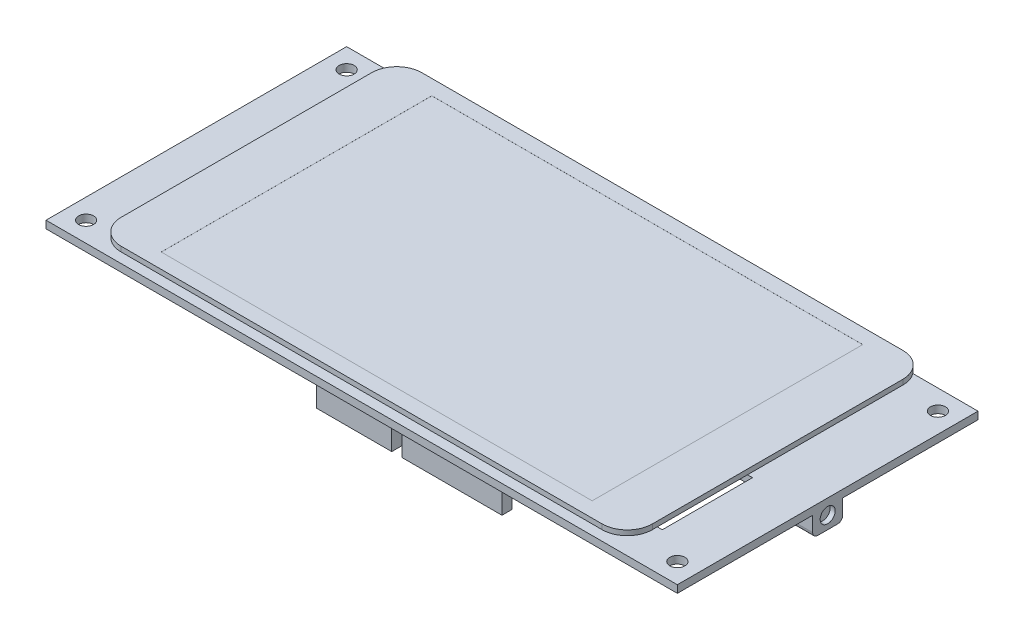
SolidWorks part; units mm, degrees
ref_plane "Front Plane" through (0, 0, 0) normal (0, 0, 1) x (1, 0, 0)
ref_plane "Top Plane" through (0, 0, 0) normal (0, 1, 0) x (1, 0, 0)
ref_plane "Right Plane" through (0, 0, 0) normal (1, 0, 0) x (0, 0, -1)
sketch "Sketch1" plane through (0, 0, 0) normal (0, 1, 0) x (1, 0, 0)
  line L0 (0, 0) -> (-26.909, 0) construction
  line L1 (-63, -30) -> (63, -30)
  line L2 (-63, -30) -> (-63, 30)
  line L3 (-63, 30) -> (63, 30)
  line L4 (63, -30) -> (63, 30)
  line L5 (-63, -30) -> (63, 30) construction
  line L6 (-63, 30) -> (63, -30) construction
  line L7 (0, 20.9021) -> (0, 0) construction
  circle A0 centre (-59, 26) radius 1.5
  circle A1 centre (-59, -26) radius 1.5
  circle A2 centre (59, -26) radius 1.5
  circle A3 centre (59, 26) radius 1.5
  point P0 (0, 0)
  dimension "D3" = 3
  dimension "D1" = 126
  dimension "D2" = 60
  dimension "D4" = 26
  dimension "D5" = 4
extrude "Boss-Extrude1" add sketch "Sketch1" along normal blind 1.5
sketch "Sketch2" plane through (0, 1.5, 0) normal (0, 1, 0) x (1, 0, 0)
  line L1 (-50, -25) -> (50, -25)
  line L2 (-50, -25) -> (-50, 25)
  line L3 (-50, 25) -> (50, 25)
  line L4 (50, -25) -> (50, 25)
  line L5 (-50, -25) -> (50, 25) construction
  line L6 (-50, 25) -> (50, -25) construction
  point P0 (0, 0)
  dimension "D1" = 100
  dimension "D2" = 50
extrude "Boss-Extrude2" add sketch "Sketch2" along normal blind 2
sketch "Sketch3" plane through (0, 3.5, 0) normal (0, 1, 0) x (1, 0, 0)
  line L0 (63, 30) -> (-63, 30) construction
  line L1 (-53, -30) -> (53, -30)
  line L2 (-53, -30) -> (-53, 30)
  line L3 (-53, 30) -> (53, 30)
  line L4 (53, -30) -> (53, 30)
  line L5 (-53, -30) -> (53, 30) construction
  line L6 (-53, 30) -> (53, -30) construction
  point P0 (0, 0)
  dimension "D1" = 106
extrude "Boss-Extrude3" add sketch "Sketch3" along normal blind 1
fillet "Fillet1" radius 5 4 edges at (-53, 4, -30) (-53, 4, 30) (53, 4, -30) (53, 4, 30)
sketch "Sketch4" plane through (0, 4.5, 0) normal (0, 1, 0) x (1, 0, 0)
  line L0 (48, 30) -> (-48, 30) construction
  line L1 (-43, -27) -> (43, -27)
  line L2 (-43, -27) -> (-43, 27)
  line L3 (-43, 27) -> (43, 27)
  line L4 (43, -27) -> (43, 27)
  line L5 (-43, -27) -> (43, 27) construction
  line L6 (-43, 27) -> (43, -27) construction
  line L7 (53, -25) -> (53, 25) construction
  point P0 (0, 0)
  dimension "D1" = 3
  dimension "D2" = 10
extrude "Cut-Extrude1" cut sketch "Sketch4" against normal blind 0.01
sketch "Sketch6" plane through (0, 0, 0) normal (0, -1, 0) x (1, 0, 0)
  line L0 (-63, 30) -> (63, 30) construction
  line L1 (34, 22) -> (52, 22)
  line L2 (34, 22) -> (34, 4)
  line L3 (34, 4) -> (52, 4)
  line L4 (52, 22) -> (52, 4)
  line L5 (63, 30) -> (63, -30) construction
  dimension "D1" = 8
  dimension "D2" = 11
  dimension "D3" = 18
  dimension "D4" = 18
extrude "Cut-Extrude2" cut sketch "Sketch6" against normal blind 1.5
sketch "Sketch7" plane through (0, 0, 0) normal (0, -1, 0) x (1, 0, 0)
  line L0 (63, 30) -> (63, -30) construction
  line L1 (3, 25) -> (23, 25)
  line L2 (3, 25) -> (3, 23)
  line L3 (3, 23) -> (23, 23)
  line L4 (23, 25) -> (23, 23)
  line L5 (-63, 30) -> (63, 30) construction
  line L7 (1, 25) -> (-14, 25)
  line L8 (1, 25) -> (1, 23)
  line L9 (1, 23) -> (-14, 23)
  line L10 (-14, 25) -> (-14, 23)
  line L11 (63, -30) -> (-63, -30) construction
  line L12 (33, -23) -> (8, -23)
  line L13 (33, -23) -> (33, -25)
  line L14 (33, -25) -> (8, -25)
  line L15 (8, -23) -> (8, -25)
  line L17 (6, -25) -> (-14, -25)
  line L18 (6, -25) -> (6, -23)
  line L19 (6, -23) -> (-14, -23)
  line L20 (-14, -25) -> (-14, -23)
  point P22 (0, -30)
  dimension "D1" = 40
  dimension "D2" = 5
  dimension "D3" = 2
  dimension "D4" = 20
  dimension "D5" = 15
  dimension "D6" = 2
  dimension "D7" = 5
  dimension "D8" = 2
  dimension "D9" = 2
  dimension "D10" = 5
  dimension "D11" = 30
  dimension "D12" = 25
  dimension "D13" = 20
  dimension "D14" = 2
  dimension "D15" = 2
  dimension "D16" = 5
extrude "Boss-Extrude4" add sketch "Sketch7" along normal blind 9
sketch "Sketch8" plane through (0, 0, -25) normal (0, 0, -1) x (-1, 0, 0)
  line L0 (-8, -9) -> (-33, -9) construction
  line L1 (-33, 0) -> (-30, 0)
  line L2 (-33, 0) -> (-33, -9)
  line L3 (-33, -9) -> (-30, -9)
  line L4 (-30, 0) -> (-30, -9)
  dimension "D1" = 3
extrude "Cut-Extrude3" cut sketch "Sketch8" against normal blind 2
sketch "Sketch9" plane through (0, 0, 0) normal (0, -1, 0) x (1, 0, 0)
  line L0 (63, 30) -> (63, -30) construction
  line L1 (58, -3) -> (63, -3)
  line L2 (58, -3) -> (58, 3)
  line L3 (58, 3) -> (63, 3)
  line L4 (63, -3) -> (63, 3)
  line L5 (58, -3) -> (63, 3) construction
  line L6 (58, 3) -> (63, -3) construction
  point P0 (60.5, 0)
  dimension "D1" = 6
  dimension "D2" = 5
extrude "Boss-Extrude5" add sketch "Sketch9" along normal blind 4
sketch "Sketch10" plane through (63, 0, 0) normal (1, 0, 0) x (0, 0, -1)
  circle A0 centre (0, -1.4695) radius 1.5
  dimension "D1" = 3
extrude "Cut-Extrude4" cut sketch "Sketch10" against normal blind 1
fillet "Fillet2" radius 1 2 edges at (60.5, -4, 3) (60.5, -4, -3)
